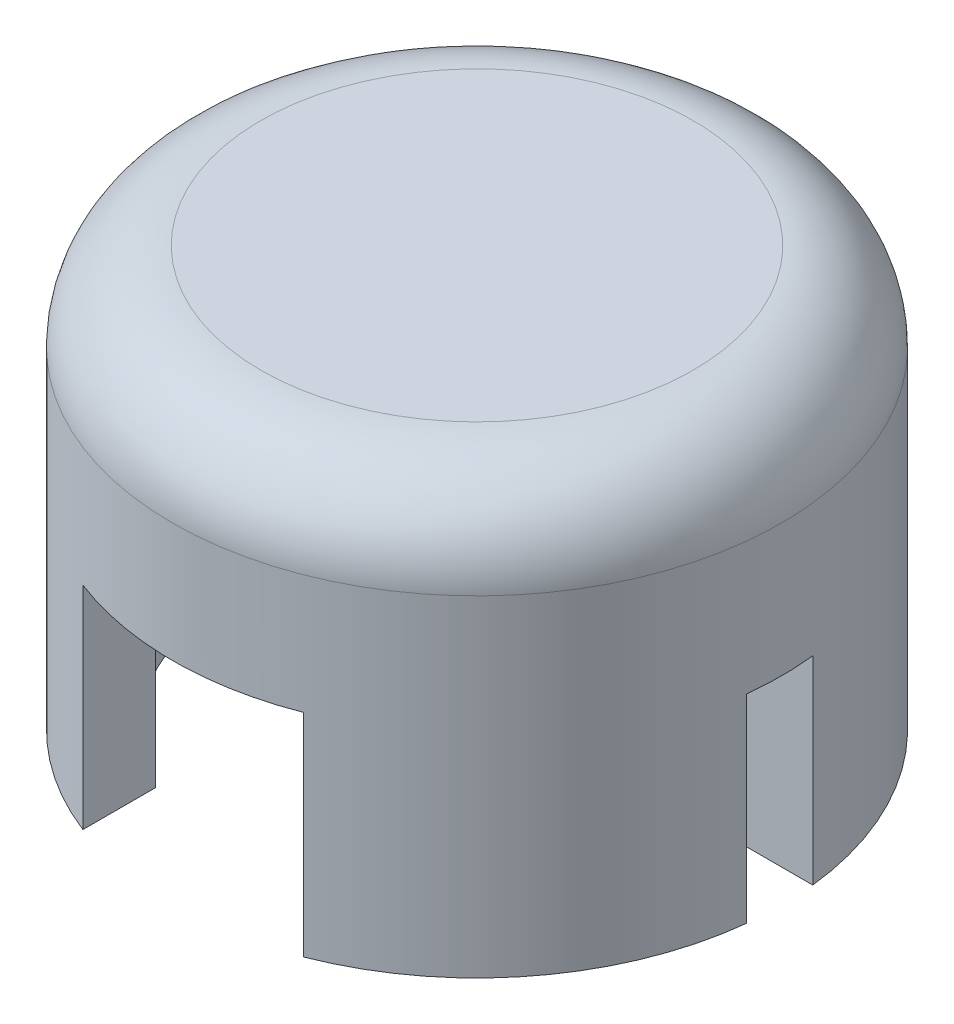
SolidWorks part; units mm, degrees
ref_plane "Front Plane" through (0, 0, 0) normal (0, 0, 1) x (1, 0, 0)
ref_plane "Top Plane" through (0, 0, 0) normal (0, 1, 0) x (1, 0, 0)
ref_plane "Right Plane" through (0, 0, 0) normal (1, 0, 0) x (0, 0, -1)
ref_axis "Axis1" through (0, 9.975, 0) along (0, -1, 0)
sketch "Sketch1" plane through (0, 0, 0) normal (0, 1, 0) x (1, 0, 0)
  circle A0 centre (0, 0) radius 6.9
  circle A1 centre (0, 0) radius 5.4
  dimension "D1" = 13.8
  dimension "D2" = 10.8
extrude "Boss-Extrude1" add sketch "Sketch1" along normal blind 7.3
sketch "Sketch2" plane through (0, 7.3, 0) normal (0, 1, 0) x (1, 0, 0)
  circle A0 centre (0, 0) radius 6.9
  dimension "D1" = 13.8
extrude "Boss-Extrude2" add sketch "Sketch2" along normal blind 2.2
fillet "Fillet1" radius 2 1 edges at (0, 9.5, 6.9)
sketch "Sketch6" plane through (0, 0, 0) normal (0, 0, 1) x (1, 0, 0)
  line L0 (0, 0) -> (5.5, 0) construction
  line L1 (5.5, 0) -> (5.5, 3.8) construction
  line L2 (5.5, 3.8) -> (5.5, 4.8)
  line L12 (5.5, 3.8) -> (4.4, 3.8)
  line L13 (5.5, 4.8) -> (4.4, 4.8)
  line L14 (4.4, 3.8) -> (4.4, 4.8)
  dimension "D1" = 5.5
  dimension "D2" = 3.8
  dimension "D3" = 1
  dimension "D4" = 1.1
revolve "Revolve3" add sketch "Sketch6" angle 360 about axis through (0, 9.975, 0) along (0, -1, 0)
sketch "Sketch4" plane through (0, 0, 0) normal (0, 0, 1) x (1, 0, 0)
  line L0 (0, 0) -> (2.5, 0) construction
  line L1 (-5.4, 0) -> (5.4, 0) construction
  line L3 (2.5, 0) -> (-2.5, 0)
  line L4 (2.5, 0) -> (2.5, 4.8)
  line L5 (2.5, 4.8) -> (-2.5, 4.8)
  line L6 (-2.5, 0) -> (-2.5, 4.8)
  dimension "D1" = 2.5
  dimension "D2" = 4.8
  dimension "D3" = 5
extrude "Cut-Extrude1" cut sketch "Sketch4" along normal through all
sketch "Sketch5" plane through (0, 0, 0) normal (1, 0, 0) x (0, 0, -1)
  line L0 (0, 0) -> (-0.75, 0) construction
  line L1 (-4.7864, 0) -> (5.4, 0) construction
  line L3 (-0.75, 0) -> (0.75, 0)
  line L4 (-0.75, 0) -> (-0.75, 4.5)
  line L5 (-0.75, 4.5) -> (0.75, 4.5)
  line L6 (0.75, 0) -> (0.75, 4.5)
  dimension "D1" = 0.75
  dimension "D2" = 1.5
  dimension "D3" = 4.5
extrude "Cut-Extrude2" cut sketch "Sketch5" against normal through all both and the other way through all
sketch "Sketch3" plane through (0, 7.3, 0) normal (0, -1, 0) x (1, 0, 0)
  circle A0 centre (0, 0) radius 3
  dimension "D1" = 6
extrude "Boss-Extrude3" add sketch "Sketch3" along normal blind 3
equation "\"outer_d\"= \"inner_d\" + 3"
equation "\"D1@Sketch1\"=\"outer_d\""
equation "\"inner_d\"= 10.8mm"
equation "\"height\"= 7.3mm"
equation "\"protrusion\"= 3mm"
equation "\"opening\"= 5mm"
equation "\"D2@Sketch1\"=\"inner_d\""
equation "\"D1@Boss-Extrude1\"=\"height\""
equation "\"D1@Sketch2\"=\"outer_d\""
equation "\"protusion_d\"= 6mm"
equation "\"D1@Sketch3\"=\"protusion_d\""
equation "\"D1@Boss-Extrude3\"=\"protrusion\""
equation "\"opening_height\"= 4.8mm"
equation "\"D1@Sketch4\"=\"opening\"/2"
equation "\"D2@Sketch4\"=\"opening_height\""
equation "\"D3@Sketch4\"=\"opening\""
equation "\"sym_opening_dis\"= .75 * 2"
equation "\"sym_opening_height\"= 4.5mm"
equation "\"D1@Sketch5\"=\"sym_opening_dis\"/2"
equation "\"D2@Sketch5\"=\"sym_opening_dis\""
equation "\"D3@Sketch5\"=\"sym_opening_height\""
equation "\"D1@Sketch6\"=\"inner_d\"/2 + 0.1"
equation "\"grip_height\"= \"height\" - 3mm"
equation "\"grip_s_h\" = 1.0mm"
equation "\"grip_s_l\" = 1.0mm"
equation "\"D2@Sketch6\"=\"grip_height\"-\"grip_s_l\"/2"
equation "\"D3@Sketch6\"=\"grip_s_h\""
equation "\"D4@Sketch6\"=\"grip_s_l\"+.1"
